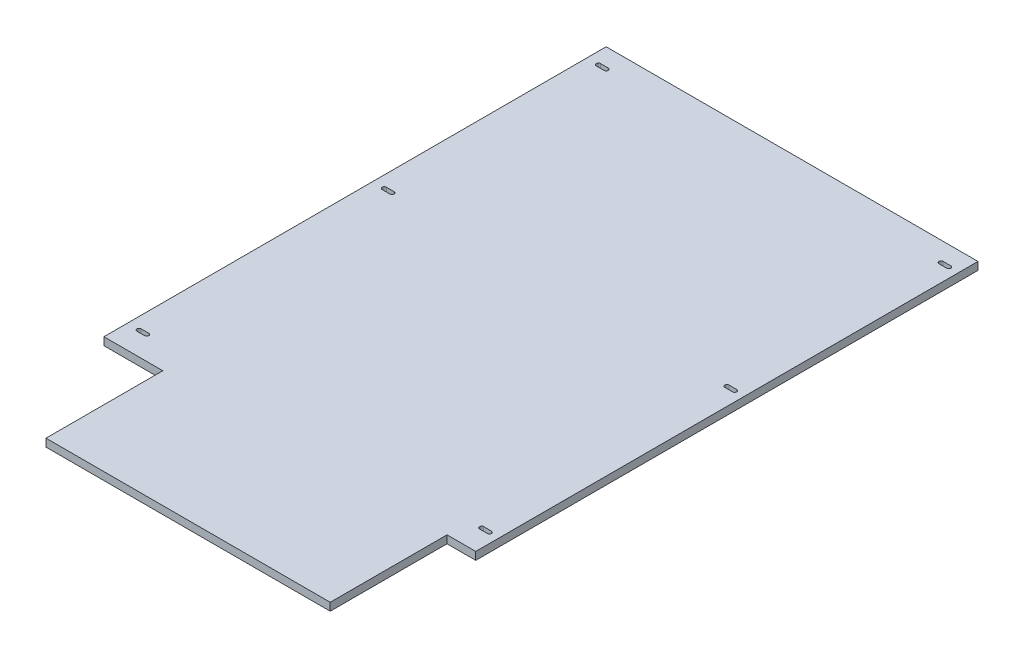
SolidWorks part; units mm, degrees
material "PE High Density"
ref_plane "Front" through (0, 0, 0) normal (0, 0, 1) x (1, 0, 0)
ref_plane "Top" through (0, 0, 0) normal (0, 1, 0) x (1, 0, 0)
ref_plane "Right" through (0, 0, 0) normal (1, 0, 0) x (0, 0, -1)
sketch "Sketch1" plane through (0, 0, 0) normal (0, 1, 0) x (1, 0, 0)
  line L0 (0, 0) -> (96.0438, 0)
  line L1 (96.0438, 0) -> (96.0438, -190.5)
  line L2 (96.0438, -190.5) -> (559.5938, -190.5)
  line L3 (559.5938, -190.5) -> (559.5938, 0)
  line L4 (559.5938, 0) -> (606.425, 0)
  line L5 (606.425, 0) -> (606.425, 819.15)
  line L6 (606.425, 819.15) -> (0, 819.15)
  line L7 (0, 819.15) -> (0, 0)
  line L8 (25.4, 0) -> (25.4, 819.15) construction
  line L9 (19.05, 38.1) -> (31.75, 38.1) construction
  line L10 (19.05, 41.4782) -> (31.75, 41.4782)
  line L11 (19.05, 34.7218) -> (31.75, 34.7218)
  line L12 (19.05, 438.15) -> (31.75, 438.15) construction
  line L13 (19.05, 441.5282) -> (31.75, 441.5282)
  line L14 (19.05, 434.7718) -> (31.75, 434.7718)
  line L15 (31.75, 787.4) -> (19.05, 787.4) construction
  line L16 (31.75, 784.0218) -> (19.05, 784.0218)
  line L17 (31.75, 790.7782) -> (19.05, 790.7782)
  line L18 (303.2125, 819.15) -> (303.2125, -190.5) construction
  line L19 (584.2, 787.4) -> (584.2, 438.15) construction
  line L20 (577.85, 787.4) -> (590.55, 787.4) construction
  line L21 (577.85, 784.0218) -> (590.55, 784.0218)
  line L22 (577.85, 790.7782) -> (590.55, 790.7782)
  line L23 (590.55, 438.15) -> (577.85, 438.15) construction
  line L24 (590.55, 441.5282) -> (577.85, 441.5282)
  line L25 (590.55, 434.7718) -> (577.85, 434.7718)
  line L26 (590.55, 38.1) -> (577.85, 38.1) construction
  line L27 (590.55, 41.4782) -> (577.85, 41.4782)
  line L28 (590.55, 34.7218) -> (577.85, 34.7218)
  line L29 (327.8187, -190.5) -> (327.8187, 819.15) construction
  line L30 (584.2, 438.15) -> (584.2, 38.1) construction
  arc A1 (19.05, 41.4782) -> (19.05, 34.7218) centre (19.05, 38.1) ccw
  arc A2 (31.75, 34.7218) -> (31.75, 41.4782) centre (31.75, 38.1) ccw
  arc A3 (19.05, 441.5282) -> (19.05, 434.7718) centre (19.05, 438.15) ccw
  arc A4 (31.75, 434.7718) -> (31.75, 441.5282) centre (31.75, 438.15) ccw
  arc A5 (31.75, 784.0218) -> (31.75, 790.7782) centre (31.75, 787.4) ccw
  arc A6 (19.05, 790.7782) -> (19.05, 784.0218) centre (19.05, 787.4) ccw
  arc A7 (577.85, 784.0218) -> (577.85, 790.7782) centre (577.85, 787.4) cw
  arc A8 (590.55, 790.7782) -> (590.55, 784.0218) centre (590.55, 787.4) cw
  arc A9 (590.55, 441.5282) -> (590.55, 434.7718) centre (590.55, 438.15) cw
  arc A10 (577.85, 434.7718) -> (577.85, 441.5282) centre (577.85, 438.15) cw
  arc A11 (590.55, 41.4782) -> (590.55, 34.7218) centre (590.55, 38.1) cw
  arc A12 (577.85, 34.7218) -> (577.85, 41.4782) centre (577.85, 38.1) cw
  point P13 (25.4, 38.1)
  point P20 (25.4, 438.15)
  point P27 (25.4, 787.4)
  point P38 (584.2, 787.4)
  point P45 (584.2, 438.15)
  point P52 (584.2, 38.1)
  dimension "D1" = 96.0438
  dimension "D2" = 46.8312
  dimension "D3" = 819.15
  dimension "D4" = 25.4
  dimension "D5" = 6.7564
  dimension "D6" = 38.1
  dimension "D7" = 12.7
  dimension "D8" = 400.05
  dimension "D9" = 349.25
  dimension "D10" = 190.5
  dimension "D11" = 463.55
  dimension "D12" = 22.225
extrude "Boss-Extrude1" add sketch "Sketch1" along normal blind 12.7
fillet "Fillet1" [suppressed] radius 6.604
fillet "Fillet2" [suppressed] radius 6.604
sketch "Sketch2" plane through (0, 12.7, 0) normal (0, 1, 0) x (1, 0, 0)
  line L1 (606.425, 0) -> (606.425, 819.15) construction
  line L3 (577.85, 438.15) -> (590.55, 438.15) construction
  line L4 (606.425, 505.867) -> (606.425, 461.873)
  line L5 (606.425, 483.87) -> (47.625, 483.87) construction
  line L6 (0, 819.15) -> (0, 0) construction
  arc A3 (600.075, 494.8685) -> (600.075, 472.8715) centre (606.425, 483.87) ccw
  arc A4 (600.075, 494.8685) -> (606.425, 505.867) centre (593.725, 505.867) ccw
  arc A5 (606.425, 461.873) -> (600.075, 472.8715) centre (593.725, 461.873) ccw
  circle A6 centre (47.625, 483.87) radius 12.7
  dimension "D1" = 25.4
  dimension "D2" = 45.72
  dimension "D3" = 47.625
extrude "Cut-Extrude1" [suppressed] cut sketch "Sketch2" against normal through all
sketch "Sketch4" plane through (0, 0, 0) normal (0, -1, 0) x (1, 0, 0)
  line L0 (0, -819.15) -> (0, 0) construction
  line L3 (327.025, -527.05) -> (327.025, -549.275) construction
  line L4 (350.8375, -527.05) -> (350.8375, -549.275)
  line L5 (303.2125, -527.05) -> (303.2125, -549.275)
  line L7 (606.425, -819.15) -> (0, -819.15) construction
  line L8 (327.025, 0) -> (327.025, -22.225) construction
  line L9 (350.8375, 0) -> (350.8375, -22.225)
  line L10 (303.2125, 0) -> (303.2125, -22.225)
  circle A0 centre (327.025, -538.1625) radius 28.575 construction
  arc A2 (350.8375, -527.05) -> (303.2125, -527.05) centre (327.025, -527.05) ccw
  arc A3 (303.2125, -549.275) -> (350.8375, -549.275) centre (327.025, -549.275) ccw
  arc A4 (350.8375, 0) -> (303.2125, 0) centre (327.025, 0) ccw
  arc A5 (303.2125, -22.225) -> (350.8375, -22.225) centre (327.025, -22.225) ccw
  point P8 (327.025, -11.1125)
  point P12 (327.025, -538.1625)
  dimension "D2" = 57.15
  dimension "D1" = 327.025
  dimension "D3" = 527.05
  dimension "D4" = 47.625
  dimension "D5" = 22.225
  dimension "D6" = 280.9875
extrude "Cut-Extrude3" [suppressed] cut sketch "Sketch4" against normal through all
sketch "Sketch5" [suppressed] plane through (0, 0, 0) normal (0, -1, 0) x (1, 0, 0)
  line L0 (327.025, -22.225) -> (327.025, -527.05) construction
  line L1 (327.025, -466.725) -> (327.025, -82.55) construction
  line L2 (320.675, -466.725) -> (320.675, -82.55)
  line L3 (333.375, -466.725) -> (333.375, -82.55)
  arc A0 (320.675, -466.725) -> (333.375, -466.725) centre (327.025, -466.725) ccw
  arc A1 (333.375, -82.55) -> (320.675, -82.55) centre (327.025, -82.55) ccw
  point P6 (327.025, -274.6375)
  dimension "D1" = 384.175
  dimension "D2" = 12.7
extrude "Cut-Extrude4" [suppressed] cut sketch "Sketch5" against normal through all
sketch "Sketch6" [suppressed] plane through (0, 0, 0) normal (0, -1, 0) x (1, 0, 0)
  line L0 (327.025, -82.55) -> (327.025, -466.725) construction
  line L1 (327.025, -274.6375) -> (354.0125, -274.6375) construction
  line L2 (354.0125, -122.2375) -> (354.0125, -427.0375) construction
  line L3 (300.0375, -122.2375) -> (300.0375, -427.0375) construction
  circle A0 centre (354.0125, -274.6375) radius 3.3782
  circle A1 centre (354.0125, -427.0375) radius 3.3782
  circle A2 centre (354.0125, -122.2375) radius 3.3782
  circle A3 centre (300.0375, -427.0375) radius 3.3782
  circle A4 centre (300.0375, -274.6375) radius 3.3782
  circle A5 centre (300.0375, -122.2375) radius 3.3782
  dimension "D2" = 6.7564
  dimension "D1" = 26.9875
  dimension "D3" = 152.4
extrude "Cut-Extrude5" [suppressed] cut sketch "Sketch6" against normal through all
sketch "Sketch7" [suppressed] plane through (0, 0, 0) normal (0, -1, 0) x (1, 0, 0)
  line L0 (599.821, -819.15) -> (6.604, -819.15) construction
  line L1 (6.604, 0) -> (89.4398, 0) construction
  line L2 (0, -812.546) -> (0, -6.604) construction
  line L3 (7.366, -819.15) -> (6.604, -819.15)
  line L4 (6.604, 0) -> (7.366, 0)
  line L5 (0, -812.546) -> (0, -6.604)
  line L6 (0.762, -6.604) -> (0.762, -812.546)
  line L7 (566.1978, 0) -> (599.821, 0) construction
  line L8 (606.425, -505.867) -> (606.425, -812.546) construction
  line L9 (606.425, -6.604) -> (606.425, -461.873) construction
  line L10 (566.1978, 0) -> (599.821, 0)
  line L11 (599.821, -819.15) -> (6.604, -819.15)
  line L12 (606.425, -505.867) -> (606.425, -812.546)
  line L13 (606.425, -6.604) -> (606.425, -461.873)
  line L14 (605.663, -504.5472) -> (605.663, -812.546)
  line L15 (605.663, -6.604) -> (605.663, -462.3309)
  arc A0 (0, -812.546) -> (6.604, -819.15) centre (6.604, -812.546) ccw construction
  arc A1 (6.604, 0) -> (0, -6.604) centre (6.604, -6.604) ccw construction
  arc A2 (0, -812.546) -> (6.604, -819.15) centre (6.604, -812.546) ccw
  arc A3 (6.604, 0) -> (0, -6.604) centre (6.604, -6.604) ccw
  arc A4 (7.366, 0) -> (0.762, -6.604) centre (7.366, -6.604) ccw
  arc A5 (0.762, -812.546) -> (7.366, -819.15) centre (7.366, -812.546) ccw
  arc A7 (606.425, -505.867) -> (600.075, -494.8685) centre (593.725, -505.867) ccw construction
  arc A8 (600.075, -472.8715) -> (600.075, -494.8685) centre (606.425, -483.87) ccw construction
  arc A9 (600.075, -472.8715) -> (606.425, -461.873) centre (593.725, -461.873) ccw construction
  arc A11 (599.821, -819.15) -> (606.425, -812.546) centre (599.821, -812.546) ccw
  arc A12 (606.425, -505.867) -> (600.075, -494.8685) centre (593.725, -505.867) ccw
  arc A13 (600.075, -472.8715) -> (600.075, -494.8685) centre (606.425, -483.87) ccw
  arc A14 (600.075, -472.8715) -> (606.425, -461.873) centre (593.725, -461.873) ccw
  arc A15 (606.425, -6.604) -> (599.821, 0) centre (599.821, -6.604) ccw
  arc A16 (605.663, -6.604) -> (599.059, 0) centre (599.059, -6.604) ccw
  arc A17 (599.059, -819.15) -> (605.663, -812.546) centre (599.059, -812.546) ccw
  arc A18 (605.663, -504.5472) -> (600.075, -494.8685) centre (594.487, -504.5472) ccw
  arc A19 (599.694, -473.1004) -> (605.663, -462.3309) centre (592.963, -462.3309) ccw
  dimension "D1" = 0.762
  dimension "D2" = 0.762
extrude "Cut-Extrude6" [suppressed] cut sketch "Sketch7" against normal through all contours A18 L14 A17 L11 A11 L12 A12 | A5 L6 A4 L4 A3 L5 A2 L3 | A19 A13 A14 L13 A15 L10 A16 L15
sketch "Sketch8" [suppressed] plane through (0, 12.7, 0) normal (0, 1, 0) x (1, 0, 0)
  line L0 (7.366, 0) -> (89.4398, 0) construction
  line L1 (599.059, 819.15) -> (7.366, 819.15) construction
  line L2 (0.762, 6.604) -> (0.762, 812.546) construction
  line L3 (7.366, 0) -> (16.891, 0)
  line L4 (16.891, 819.15) -> (7.366, 819.15)
  line L5 (0.762, 6.604) -> (0.762, 812.546)
  line L6 (10.287, 6.604) -> (10.287, 812.546)
  line L7 (602.488, 6.604) -> (602.488, 812.546)
  line L8 (605.663, 504.5472) -> (605.663, 812.546) construction
  line L9 (599.059, 0) -> (595.884, 0)
  line L10 (605.663, 6.604) -> (605.663, 812.546)
  line L11 (599.059, 819.15) -> (595.884, 819.15)
  arc A0 (0.762, 6.604) -> (7.366, 0) centre (7.366, 6.604) ccw construction
  arc A1 (7.366, 819.15) -> (0.762, 812.546) centre (7.366, 812.546) ccw construction
  arc A2 (0.762, 6.604) -> (7.366, 0) centre (7.366, 6.604) ccw
  arc A3 (7.366, 819.15) -> (0.762, 812.546) centre (7.366, 812.546) ccw
  arc A4 (10.287, 6.604) -> (16.891, 0) centre (16.891, 6.604) ccw
  arc A5 (16.891, 819.15) -> (10.287, 812.546) centre (16.891, 812.546) ccw
  arc A6 (599.059, 0) -> (605.663, 6.604) centre (599.059, 6.604) ccw construction
  arc A7 (599.059, 0) -> (605.663, 6.604) centre (599.059, 6.604) ccw
  arc A8 (605.663, 812.546) -> (599.059, 819.15) centre (599.059, 812.546) ccw construction
  arc A9 (605.663, 812.546) -> (599.059, 819.15) centre (599.059, 812.546) ccw
  arc A10 (602.488, 812.546) -> (595.884, 819.15) centre (595.884, 812.546) ccw
  arc A11 (595.884, 0) -> (602.488, 6.604) centre (595.884, 6.604) ccw
  dimension "D2" = 9.525
  dimension "D4" = 3.175
  dimension "D1" = 2
  dimension "D3" = 2
extrude "Cut-Extrude7" [suppressed] cut sketch "Sketch8" against normal through all contours A5 L4 A3 L5 A2 L3 A4 L6 | L11 A10 L7 A11 L9 A7 L10 A9
fillet "Fillet3" [suppressed] radius 3.175
